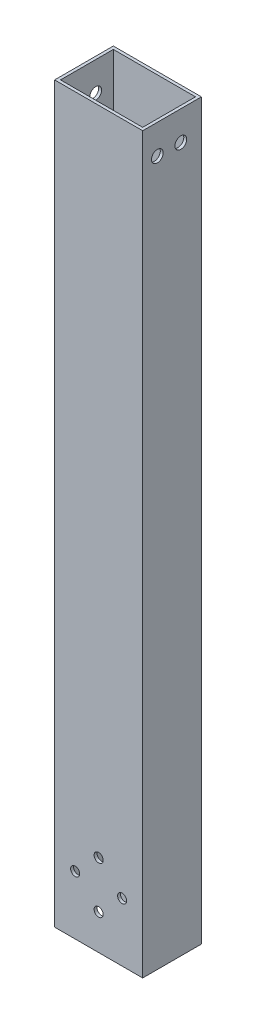
SolidWorks part; units mm, degrees
ref_plane "前视基准面" through (0, 0, 0) normal (0, 0, 1) x (1, 0, 0)
ref_plane "上视基准面" through (0, 0, 0) normal (0, 1, 0) x (1, 0, 0)
ref_plane "右视基准面" through (0, 0, 0) normal (1, 0, 0) x (0, 0, -1)
other "Configuration Table"
sketch "草图1" plane through (0, 0, 0) normal (0, 1, 0) x (1, 0, 0)
  line L1 (-15, -10) -> (15, -10)
  line L2 (-15, -10) -> (-15, 10)
  line L3 (-15, 10) -> (15, 10)
  line L4 (15, -10) -> (15, 10)
  line L5 (0, 10) -> (0, -10) construction
  line L6 (-15, 0) -> (15, 0) construction
  line L7 (-14, -9) -> (14, -9)
  line L8 (-14, -9) -> (-14, 9)
  line L9 (-14, 9) -> (14, 9)
  line L10 (14, -9) -> (14, 9)
  line L11 (0, 9) -> (0, -9) construction
  line L12 (-14, 0) -> (14, 0) construction
  point P0 (0, 0)
  point P4 (0, 0)
  dimension "D1" = 30
  dimension "D2" = 20
  dimension "D3" = 1
  dimension "D4" = 1
extrude "凸台-拉伸1" add sketch "草图1" along normal blind 250
sketch "草图2" plane through (0, 0, 0) normal (0, 0, 1) x (1, 0, 0)
  line L0 (0, -46.283) -> (0, 306.1037) construction
  line L1 (-83.5307, 20) -> (87.1925, 20) construction
  line L2 (0, 20) -> (0, 28) construction
  circle A0 centre (0, 28) radius 1.55
  circle A1 centre (8, 20) radius 1.55
  circle A2 centre (0, 12) radius 1.55
  circle A3 centre (-8, 20) radius 1.55
  point P7 (0, 20)
  dimension "D2" = 3.1
  dimension "D1" = 20
  dimension "D4" = 8
  dimension "D3" = 4
extrude "切除-拉伸1" cut sketch "草图2" against normal through all both and the other way through all
sketch "草图3" plane through (0, 0, 0) normal (1, 0, 0) x (0, 0, -1)
  line L0 (-82.4991, 240) -> (85.7164, 240) construction
  line L1 (-10, 250) -> (10, 250) construction
  line L2 (-10, 250) -> (-10, 0) construction
  circle A0 centre (-5, 240) radius 2
  circle A1 centre (3, 240) radius 2
  dimension "D4" = 4
  dimension "D1" = 10
  dimension "D2" = 5
  dimension "D3" = 8
extrude "切除-拉伸2" cut sketch "草图3" against normal through all both and the other way through all
